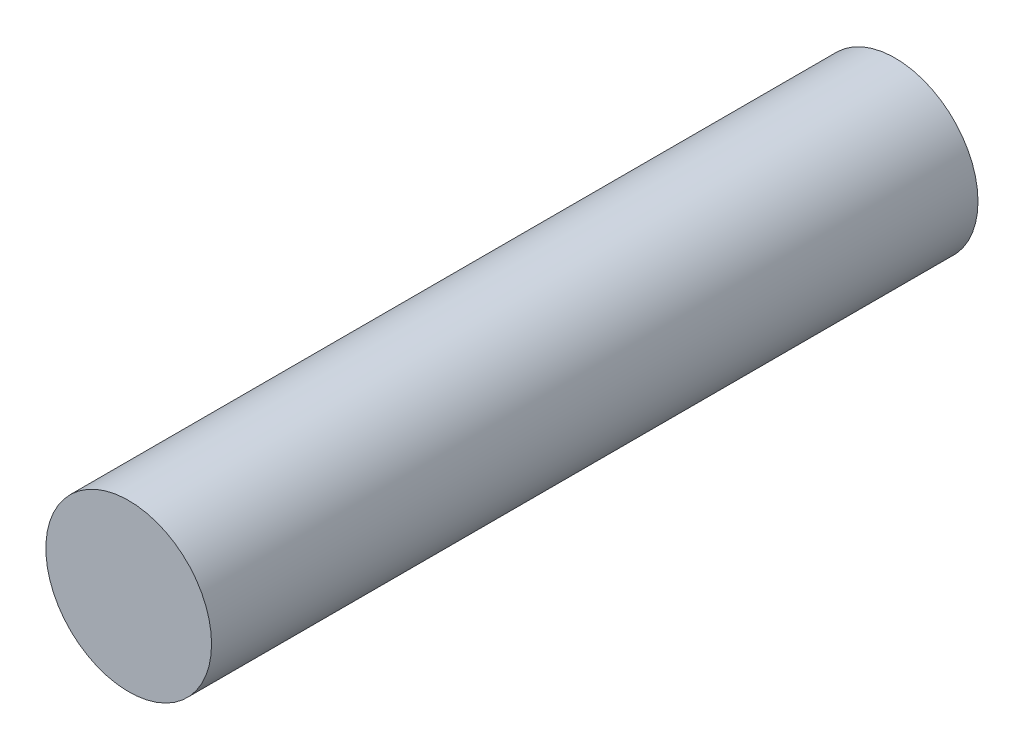
SolidWorks part; units mm, degrees
ref_plane "Front Plane" through (0, 0, 0) normal (0, 0, 1) x (1, 0, 0)
ref_plane "Top Plane" through (0, 0, 0) normal (0, 1, 0) x (1, 0, 0)
ref_plane "Right Plane" through (0, 0, 0) normal (1, 0, 0) x (0, 0, -1)
sketch "Sketch1" plane through (0, 0, 0) normal (0, 0, 1) x (1, 0, 0)
  circle A0 centre (0, 0) radius 4
  dimension "D1" = 8
extrude "Boss-Extrude1" add sketch "Sketch1" along normal blind 37
